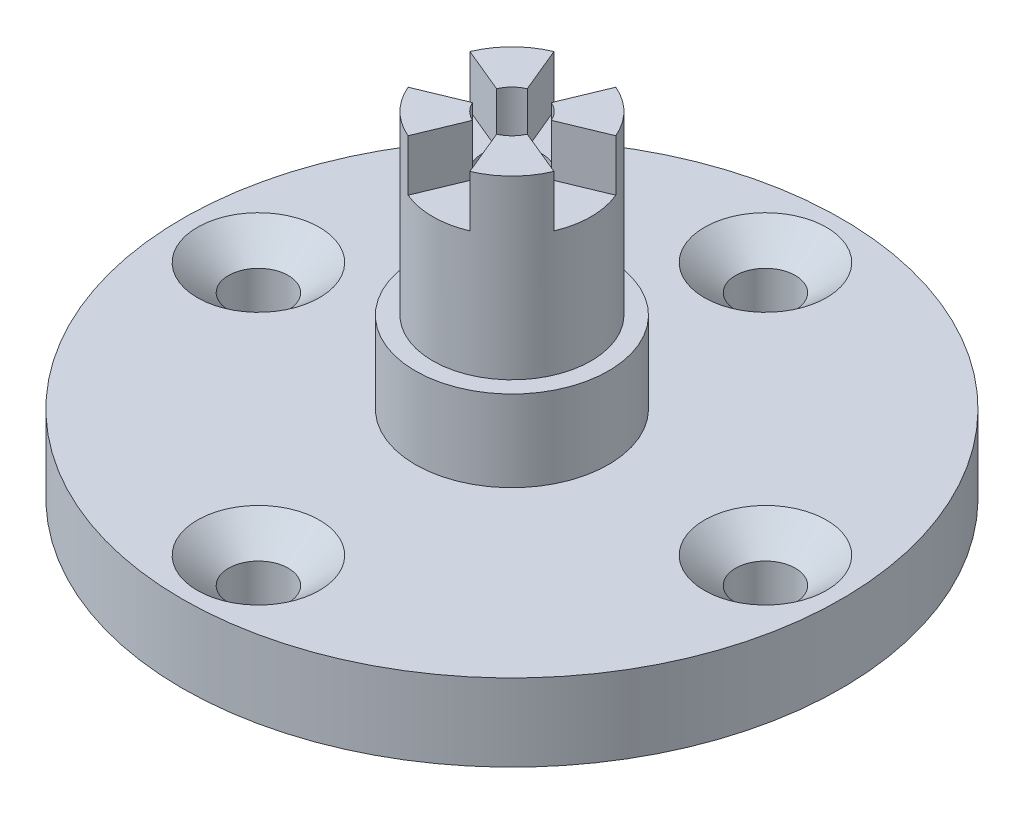
SolidWorks part; units mm, degrees
ref_plane "Front Plane" through (0, 0, 0) normal (0, 0, 1) x (1, 0, 0)
ref_plane "Top Plane" through (0, 0, 0) normal (0, 1, 0) x (1, 0, 0)
ref_plane "Right Plane" through (0, 0, 0) normal (1, 0, 0) x (0, 0, -1)
sketch "Sketch1" plane through (0, 0, 0) normal (0, 1, 0) x (1, 0, 0)
  circle A0 centre (0, 0) radius 4.7625
  dimension "D1" = 9.525
extrude "Boss-Extrude1" add sketch "Sketch1" along normal blind 10.16
sketch "Sketch3" plane through (0, 0, 0) normal (0, -1, 0) x (1, 0, 0)
  circle A9 centre (0, 0) radius 16.25
  dimension "D1" = 32.5
extrude "Boss-Extrude2" add sketch "Sketch3" along normal blind 3.81
hole_wizard "#4 Clearance Hole1" positions "Sketch4" profile "Sketch5" hole size "#4" standard "ANSI Inch" end condition through all
sketch "Sketch4" plane through (0, -3.81, 0) normal (0, -1, 0) x (-1, 0, 0)
  point P0 (0, 0)
sketch "Sketch5" plane through (0, -3.81, 0) normal (1, 0, 0) x (0, 0, -1)
  line L0 (0, 0) -> (0, 13.97)
  line L1 (0, 13.97) -> (1.4732, 13.97)
  line L2 (1.4732, 13.97) -> (1.4732, 0)
  line L5 (1.4732, 0) -> (0, 0)
  line L11 (0, -6.35) -> (0, 107.95) construction
  dimension "Thru Hole Dia." = 2.9464
  dimension "Thru Hole Depth" = 13.97
sketch "Sketch6" plane through (0, 10.16, 0) normal (0, 1, 0) x (1, 0, 0)
  circle A0 centre (0, 0) radius 3.9053
  circle A1 centre (0, 0) radius 4.7625
  circle A2 centre (0, 0) radius 4.7625 construction
  dimension "D1" = 7.8105
extrude "Cut-Extrude1" cut sketch "Sketch6" against normal blind 6.1595
sketch "Sketch7" plane through (0, -3.81, 0) normal (0, -1, 0) x (1, 0, 0)
  line L1 (-3.6662, 0) -> (-1.8331, -3.175)
  line L2 (-1.8331, -3.175) -> (1.8331, -3.175)
  line L3 (1.8331, -3.175) -> (3.6662, 0)
  line L4 (3.6662, 0) -> (1.8331, 3.175)
  line L5 (1.8331, 3.175) -> (-1.8331, 3.175)
  line L6 (-1.8331, 3.175) -> (-3.6662, 0)
  circle A0 centre (0, 0) radius 3.175 construction
  dimension "D1" = 6.35
extrude "Cut-Extrude4" cut sketch "Sketch7" against normal blind 6.35
sketch "Sketch8" plane through (0, 10.16, 0) normal (0, 1, 0) x (1, 0, 0)
  line L0 (0, 0) -> (-2.7614, 2.7614) construction
  line L1 (-0.593, 1.3486) -> (-1.5238, 3.5957)
  line L2 (-1.3486, 0.593) -> (-3.5957, 1.5238)
  line L3 (-1.4945, 3.608) -> (-0.5638, 1.3611) construction
  line L4 (0, 0) -> (0, 3.9053) construction
  line L6 (-1.3611, 0.5638) -> (-3.608, 1.4945) construction
  circle A0 centre (0, 0) radius 3.9053 construction
  circle A1 centre (0, 0) radius 1.4732 construction
  circle A2 centre (0, 0) radius 3.9053 construction
  arc A3 (-1.4945, 3.608) -> (-3.608, 1.4945) centre (0, 0) ccw construction
  arc A4 (-1.3611, 0.5638) -> (-0.5638, 1.3611) centre (0, 0) cw construction
  arc A5 (-3.5957, 1.5238) -> (-1.5238, 3.5957) centre (0, 0) cw
  arc A6 (-1.3486, 0.593) -> (-0.593, 1.3486) centre (0, 0) cw
  point P6 (-1.0417, 1.0417)
  dimension "D1" = 45
  dimension "D2" = 0.0635
  dimension "D3" = 45
extrude "Boss-Extrude3" add sketch "Sketch8" along normal blind 2.54
pattern_circular "CirPattern1" count 4 over 360 about axis through (0, 0, 0) along (0, 1, 0) of "Boss-Extrude3"
sketch "Sketch9" plane through (0, 0, 0) normal (0, 1, 0) x (1, 0, 0)
  line L0 (0, 0) -> (0, 12.5)
  dimension "D1" = 12.5
hole_wizard "CSK for #4 Flat Head Machine Screw (100)1" positions "Sketch10" profile "Sketch12" countersink size "#4" standard "ANSI Inch" end condition through all
sketch "Sketch10" plane through (0, 0, 0) normal (0, 1, 0) x (1, 0, 0)
  point P0 (0, 12.5)
sketch "Sketch12" plane through (0, 0, -12.5) normal (1, 0, 0) x (0, 0, 1)
  line L0 (0, 0) -> (0, 3.81)
  line L1 (0, 3.81) -> (1.4732, 3.81)
  line L2 (1.4732, 3.81) -> (1.4732, 1.2886)
  line L3 (1.4732, 1.2886) -> (3.0089, 0)
  line L5 (3.0089, 0) -> (0, 0)
  line L6 (-1.4732, 1.2886) -> (-3.0089, 0) construction
  line L11 (0, -6.35) -> (0, 107.95) construction
  dimension "Thru Hole Dia." = 2.9464
  dimension "Thru Hole Depth" = 3.81
  dimension "Near C'Sink Dia." = 6.0177
  dimension "Near C'Sink Angle" = 100
pattern_circular "CirPattern2" count 4 over 360 about axis through (0, 0, 0) along (0, 1, 0) of "CSK for #4 Flat Head Machine Screw (100)1"
